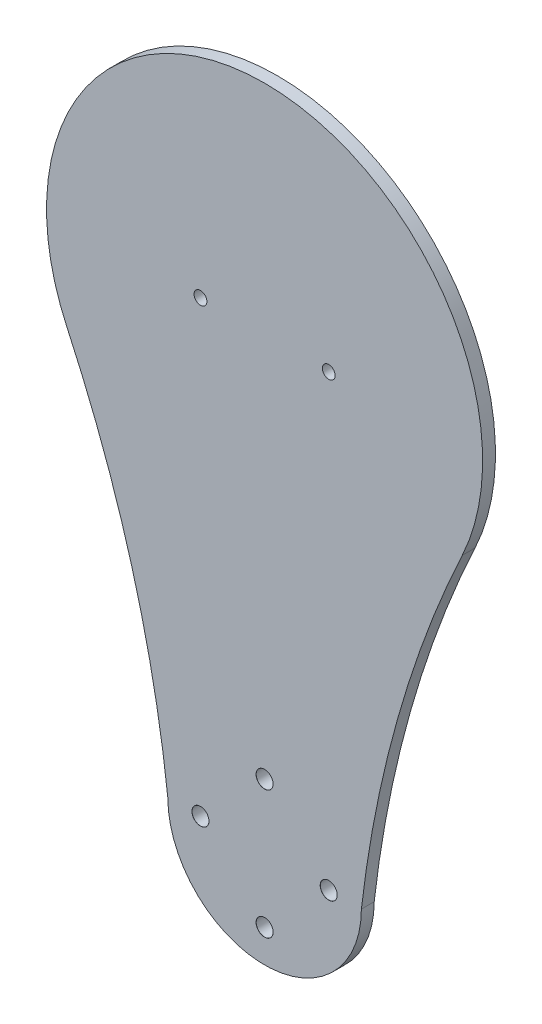
SolidWorks part; units mm, degrees
ref_plane "Front Plane" through (0, 0, 0) normal (0, 0, 1) x (1, 0, 0)
ref_plane "Top Plane" through (0, 0, 0) normal (0, 1, 0) x (1, 0, 0)
ref_plane "Right Plane" through (0, 0, 0) normal (1, 0, 0) x (0, 0, -1)
sketch "Sketch6" plane through (0, 0, 0) normal (0, 0, 1) x (1, 0, 0)
  line L0 (0, 0) -> (62.1656, 0) construction
  line L1 (62.1656, 0) -> (62.1656, 175) construction
  line L2 (62.1656, 175) -> (-62.1656, 175) construction
  line L3 (-62.1656, 175) -> (-62.1656, 0) construction
  line L4 (-62.1656, 0) -> (0, 0) construction
  line L5 (70.0261, 123.2416) -> (146.05, 67.05) construction
  line L6 (-146.05, 67.05) -> (146.05, 67.05) construction
  line L7 (-146.05, 67.05) -> (-146.05, 282.95) construction
  line L8 (-146.05, 282.95) -> (146.05, 282.95) construction
  line L9 (146.05, 67.05) -> (146.05, 282.95) construction
  line L10 (-146.05, 67.05) -> (146.05, 282.95) construction
  line L11 (-146.05, 282.95) -> (70.8378, 122.6416) construction
  arc A1 (37.73, 0) -> (77.0496, 139.1064) centre (487.0576, -51.8961) cw
  arc A3 (-37.73, 0) -> (-77.0496, 139.1064) centre (-487.0576, -51.8961) ccw
  arc A4 (77.0496, 139.1064) -> (-77.0496, 139.1064) centre (0, 175) ccw
  arc A7 (-37.73, 0) -> (37.73, 0) centre (0, 0) ccw
  point P6 (0, 175)
  dimension "D5" = 452.3145
  dimension "D1" = 292.1
  dimension "D2" = 215.9
  dimension "D3" = 175
extrude "Boss-Extrude4" add sketch "Sketch6" along normal blind 5
sketch "Sketch7" plane through (0, 0, 5) normal (0, 0, 1) x (1, 0, 0)
  circle A0 centre (0, 0) radius 25 construction
  dimension "D1" = 50
hole_wizard "M6 Clearance Hole1" positions "Sketch8" profile "Sketch9" hole size "M6" standard "ANSI Metric" end condition through all
sketch "Sketch8" plane through (0, 0, 5) normal (0, 0, 1) x (1, 0, 0)
  circle A0 centre (0, 0) radius 25 construction
  point P0 (0, 25)
  point P4 (25, 0)
  point P6 (0, -25)
  point P8 (-25, 0)
sketch "Sketch9" plane through (0, 25, 5) normal (1, 0, 0) x (0, -1, 0)
  line L0 (0, 0) -> (0, 5)
  line L1 (0, 5) -> (3.3, 5)
  line L2 (3.3, 5) -> (3.3, 0.025)
  line L3 (3.3, 0.025) -> (3.325, 0)
  line L5 (3.325, 0) -> (0, 0)
  line L6 (-3.3, 0.025) -> (-3.325, 0) construction
  line L11 (0, -6.35) -> (0, 107.95) construction
  dimension "Thru Hole Dia." = 6.6
  dimension "Thru Hole Depth" = 5
  dimension "Near C'Sink Dia." = 6.65
  dimension "Near C'Sink Angle" = 90
sketch "Sketch10" plane through (0, 0, 5) normal (0, 0, 1) x (1, 0, 0)
  line L1 (-25, 160) -> (25, 160) construction
  line L2 (-25, 160) -> (-25, 190) construction
  line L3 (-25, 190) -> (25, 190) construction
  line L4 (25, 160) -> (25, 190) construction
  line L5 (-25, 160) -> (25, 190) construction
  line L6 (-25, 190) -> (25, 160) construction
  circle A0 centre (-25, 175) radius 2.5
  circle A1 centre (25, 175) radius 2.5
  point P0 (0, 175)
  dimension "D3" = 5
  dimension "D1" = 50
  dimension "D2" = 30
extrude "Cut-Extrude1" cut sketch "Sketch10" against normal blind 5
